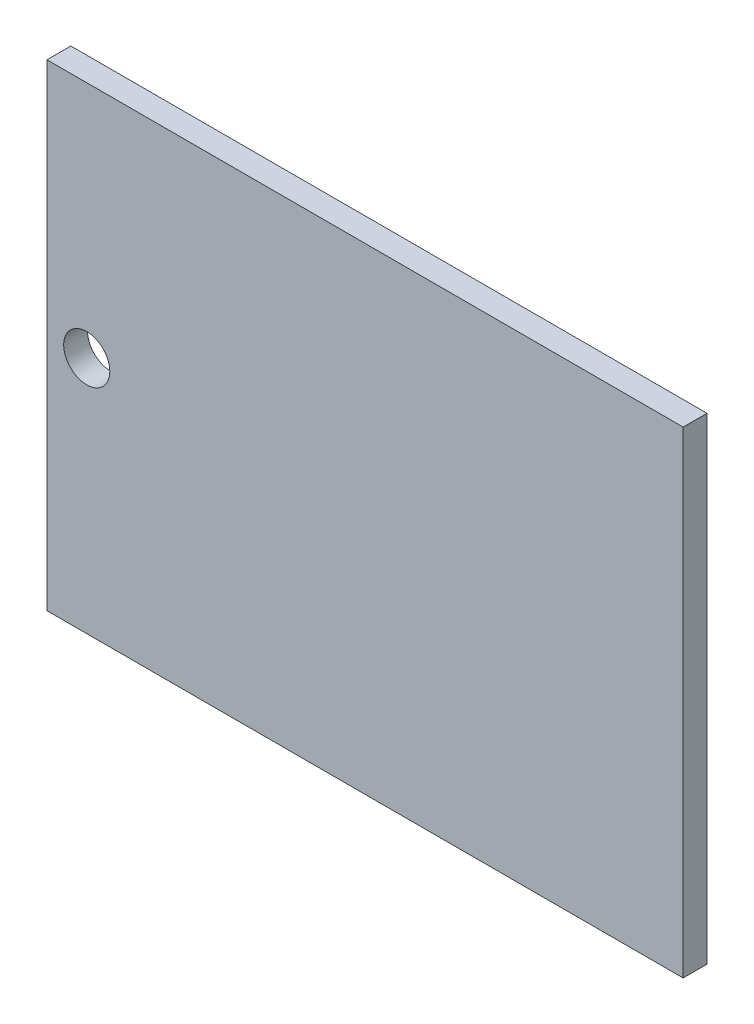
SolidWorks part; units mm, degrees
ref_plane "Front Plane" through (0, 0, 0) normal (0, 0, 1) x (1, 0, 0)
ref_plane "Top Plane" through (0, 0, 0) normal (0, 1, 0) x (1, 0, 0)
ref_plane "Right Plane" through (0, 0, 0) normal (1, 0, 0) x (0, 0, -1)
sketch "Sketch1" plane through (0, 0, 0) normal (0, 0, 1) x (1, 0, 0)
  line L1 (-20, -15) -> (20, -15)
  line L2 (-20, -15) -> (-20, 15)
  line L3 (-20, 15) -> (20, 15)
  line L4 (20, -15) -> (20, 15)
  line L5 (-20, -15) -> (20, 15) construction
  line L6 (-20, 15) -> (20, -15) construction
  point P0 (0, 0)
  dimension "D1" = 40
  dimension "D2" = 30
extrude "Boss-Extrude2" add sketch "Sketch1" along normal blind 1.5
sketch "Sketch2" plane through (0, 0, 1.5) normal (0, 0, 1) x (1, 0, 0)
  line L0 (-20, 15) -> (-20, -15) construction
  line L1 (-20, 0) -> (-17.5, 0) construction
  circle A0 centre (-17.5, 0) radius 1.45
  point P0 (-20, 0)
  dimension "D1" = 15
extrude "Cut-Extrude1" cut sketch "Sketch2" against normal through all
